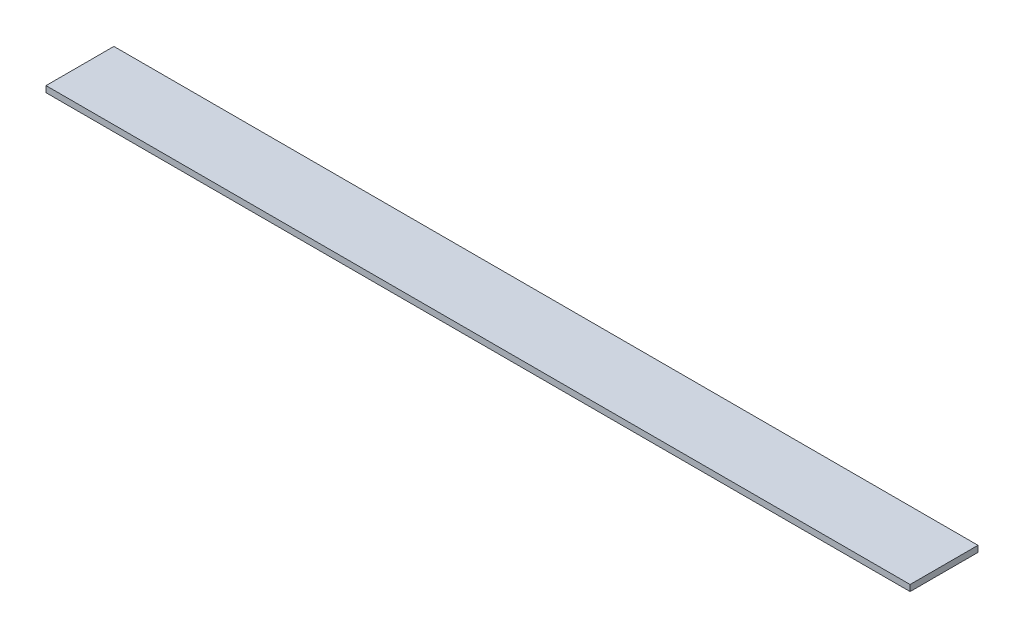
SolidWorks part; units mm, degrees
ref_plane "Front Plane" through (0, 0, 0) normal (0, 0, 1) x (1, 0, 0)
ref_plane "Top Plane" through (0, 0, 0) normal (0, 1, 0) x (1, 0, 0)
ref_plane "Right Plane" through (0, 0, 0) normal (1, 0, 0) x (0, 0, -1)
sketch "Sketch1" plane through (0, 0, 0) normal (1, 0, 0) x (0, 0, -1)
  line L1 (0, 0) -> (110, 0)
  line L2 (0, 0) -> (0, -10)
  line L3 (0, -10) -> (110, -10)
  line L4 (110, 0) -> (110, -10)
  dimension "D1" = 110
  dimension "D2" = 10
extrude "Boss-Extrude1" add sketch "Sketch1" along normal blind 1400 contours L1 L4 L3 L2
